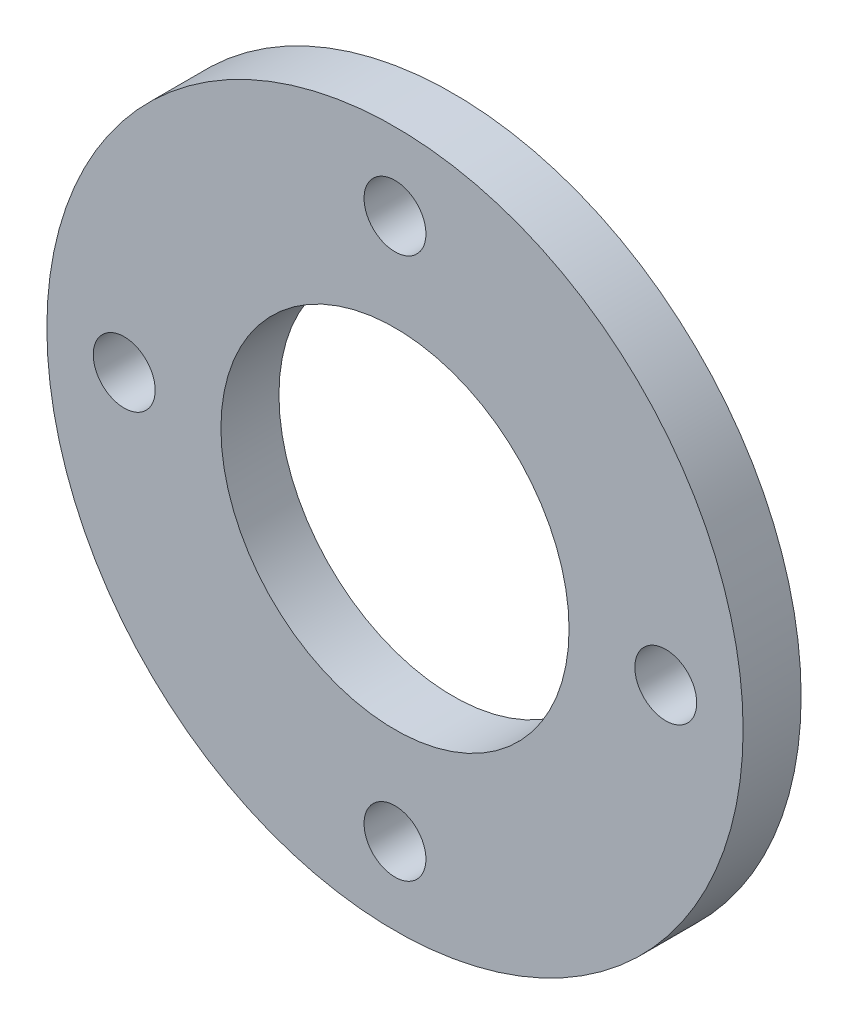
SolidWorks part; units mm, degrees
ref_plane "前视基准面" through (0, 0, 0) normal (0, 0, 1) x (1, 0, 0)
ref_plane "上视基准面" through (0, 0, 0) normal (0, 1, 0) x (1, 0, 0)
ref_plane "右视基准面" through (0, 0, 0) normal (1, 0, 0) x (0, 0, -1)
sketch "Model" plane through (0, 0, 0) normal (0, 0, 1) x (1, 0, 0)
  circle A1 centre (0, 0) radius 18
  circle A10 centre (0, 0) radius 9
  circle A11 centre (0, 14) radius 1.6
  circle A12 centre (-14, 0) radius 1.6
  circle A13 centre (0, -14) radius 1.6
  circle A14 centre (14, 0) radius 1.6
  dimension "D1" = 18
extrude "凸台-拉伸1" add sketch "Model" along normal blind 3
